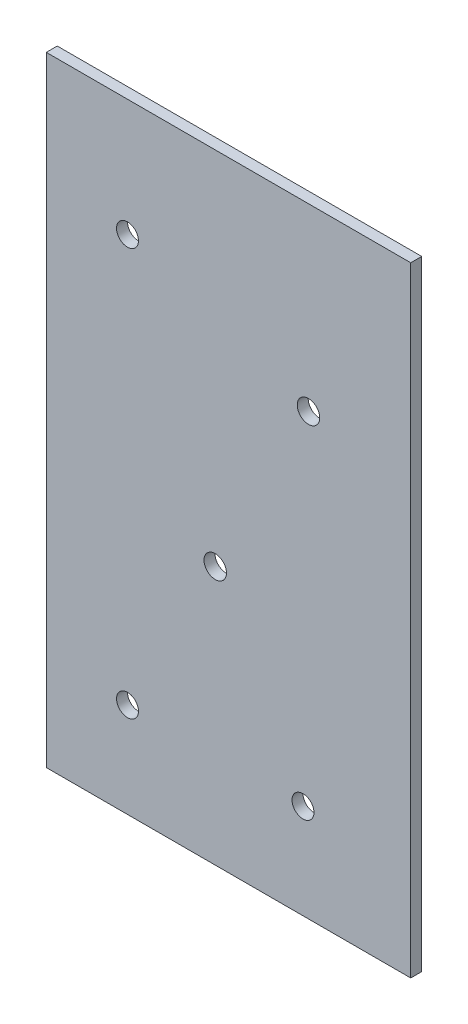
SolidWorks part; units mm, degrees
ref_plane "Front Plane" through (0, 0, 0) normal (0, 0, 1) x (1, 0, 0)
ref_plane "Top Plane" through (0, 0, 0) normal (0, 1, 0) x (1, 0, 0)
ref_plane "Right Plane" through (0, 0, 0) normal (1, 0, 0) x (0, 0, -1)
sketch "Sketch1" plane through (0, 0, 0) normal (0, 0, 1) x (1, 0, 0)
  line L0 (88.9, 95.25) -> (63.5, 95.25) construction
  line L1 (1.8891, 210.8161) -> (107.3869, 210.8161)
  line L2 (1.8891, 210.8161) -> (1.8891, 31.5173)
  line L3 (1.8891, 31.5173) -> (107.3869, 31.5173)
  line L4 (107.3869, 210.8161) -> (107.3869, 31.5173)
  line L5 (63.5, 95.25) -> (63.5, 146.05) construction
  line L8 (88.9, 95.25) -> (88.9, 146.05) construction
  circle A0 centre (25.4, 58.9643) radius 3.175
  circle A1 centre (76.2, 58.9643) radius 3.175
  circle A2 centre (25.4, 176.8929) radius 3.175
  circle A4 centre (77.7875, 158.75) radius 3.2512
  circle A6 centre (50.8, 106.3625) radius 3.2512
  dimension "D1" = 6.35
  dimension "D5" = 11.1125
  dimension "D6" = 6.5024
  dimension "D7" = 33.9233
  dimension "D9" = 27.447
  dimension "D3" = 11.1125
  dimension "D2" = 12.7
  dimension "D4" = 12.7
  dimension "D8" = 23.5109
  dimension "D10" = 31.1869
extrude "Boss-Extrude1" add sketch "Sketch1" along normal blind 3.175
equation "\"80/20 to Center Hole\"= .64in"
equation "\"80/20 from Edge\"= 0.5in"
